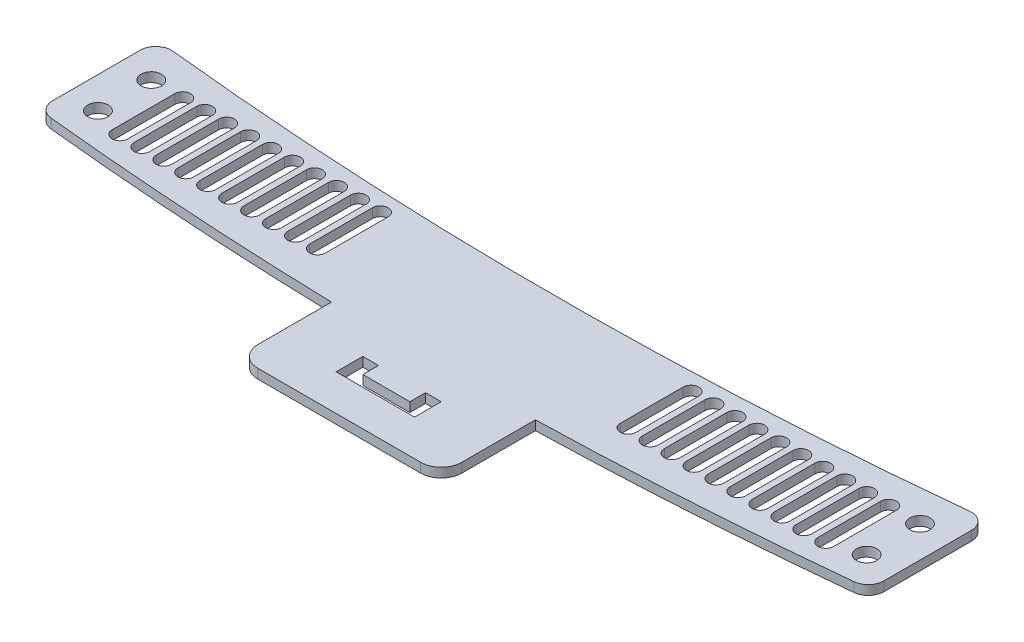
SolidWorks part; units mm, degrees
ref_plane "Front Plane" through (0, 0, 0) normal (0, 0, 1) x (1, 0, 0)
ref_plane "Top Plane" through (0, 0, 0) normal (0, 1, 0) x (1, 0, 0)
ref_plane "Right Plane" through (0, 0, 0) normal (1, 0, 0) x (0, 0, -1)
sketch "Sketch1" plane through (0, 0, 0) normal (0, 1, 0) x (1, 0, 0)
  line L0 (-10, 6.4366) -> (-10, -21.4937)
  line L5 (255, 6.4366) -> (255, -21.4937)
  line L6 (10, 0) -> (10, -20) construction
  line L7 (12.5, 0) -> (12.5, -20)
  line L8 (7.5, 0) -> (7.5, -20)
  line L9 (17, 0) -> (17, -20) construction
  line L10 (19.5, 0) -> (19.5, -20)
  line L11 (14.5, 0) -> (14.5, -20)
  line L12 (24, 0) -> (24, -20) construction
  line L13 (26.5, 0) -> (26.5, -20)
  line L14 (21.5, 0) -> (21.5, -20)
  line L15 (31, 0) -> (31, -20) construction
  line L16 (33.5, 0) -> (33.5, -20)
  line L17 (28.5, 0) -> (28.5, -20)
  line L18 (38, 0) -> (38, -20) construction
  line L19 (40.5, 0) -> (40.5, -20)
  line L20 (35.5, 0) -> (35.5, -20)
  line L21 (45, 0) -> (45, -20) construction
  line L22 (47.5, 0) -> (47.5, -20)
  line L23 (42.5, 0) -> (42.5, -20)
  line L24 (52, 0) -> (52, -20) construction
  line L25 (54.5, 0) -> (54.5, -20)
  line L26 (49.5, 0) -> (49.5, -20)
  line L27 (59, 0) -> (59, -20) construction
  line L28 (61.5, 0) -> (61.5, -20)
  line L29 (56.5, 0) -> (56.5, -20)
  line L30 (66, 0) -> (66, -20) construction
  line L31 (68.5, 0) -> (68.5, -20)
  line L32 (63.5, 0) -> (63.5, -20)
  line L33 (73, 0) -> (73, -20) construction
  line L34 (75.5, 0) -> (75.5, -20)
  line L35 (70.5, 0) -> (70.5, -20)
  line L36 (172, 0) -> (172, -20) construction
  line L37 (174.5, 0) -> (174.5, -20)
  line L38 (169.5, 0) -> (169.5, -20)
  line L39 (179, 0) -> (179, -20) construction
  line L40 (181.5, 0) -> (181.5, -20)
  line L41 (176.5, 0) -> (176.5, -20)
  line L42 (186, 0) -> (186, -20) construction
  line L43 (188.5, 0) -> (188.5, -20)
  line L44 (183.5, 0) -> (183.5, -20)
  line L45 (193, 0) -> (193, -20) construction
  line L46 (195.5, 0) -> (195.5, -20)
  line L47 (190.5, 0) -> (190.5, -20)
  line L48 (200, 0) -> (200, -20) construction
  line L49 (202.5, 0) -> (202.5, -20)
  line L50 (197.5, 0) -> (197.5, -20)
  line L51 (207, 0) -> (207, -20) construction
  line L52 (209.5, 0) -> (209.5, -20)
  line L53 (204.5, 0) -> (204.5, -20)
  line L54 (214, 0) -> (214, -20) construction
  line L55 (216.5, 0) -> (216.5, -20)
  line L56 (211.5, 0) -> (211.5, -20)
  line L57 (221, 0) -> (221, -20) construction
  line L58 (223.5, 0) -> (223.5, -20)
  line L59 (218.5, 0) -> (218.5, -20)
  line L60 (228, 0) -> (228, -20) construction
  line L61 (230.5, 0) -> (230.5, -20)
  line L62 (225.5, 0) -> (225.5, -20)
  line L63 (235, 0) -> (235, -20) construction
  line L64 (237.5, 0) -> (237.5, -20)
  line L65 (232.5, 0) -> (232.5, -20)
  line L66 (90, -32.58) -> (90, -56.0296)
  line L67 (96.5504, -62.58) -> (148.4496, -62.58)
  line L68 (155, -56.0296) -> (155, -32.58)
  line L69 (115, -42.58) -> (115, -47.58)
  line L70 (110, -42.58) -> (115, -42.58)
  line L71 (110, -42.58) -> (110, -51.08)
  line L72 (110, -51.08) -> (135, -51.08)
  line L73 (135, -42.58) -> (135, -51.08)
  line L74 (115, -47.58) -> (130, -47.58)
  line L75 (130, -47.58) -> (130, -42.58)
  line L76 (130, -42.58) -> (135, -42.58)
  circle A0 centre (0, 0) radius 3.25
  circle A1 centre (245, 0) radius 3.25
  circle A2 centre (0, -17) radius 3.25
  circle A3 centre (245, -17) radius 3.25
  arc A4 (-5.509, -26.4677) -> (90, -32.58) centre (122.5, 1224.5179) ccw
  arc A5 (-4.4795, 11.4094) -> (249.4795, 11.4094) centre (122.5, 1224.5179) ccw
  arc A6 (12.5, 0) -> (7.5, 0) centre (10, 0) ccw
  arc A7 (7.5, -20) -> (12.5, -20) centre (10, -20) ccw
  arc A8 (19.5, 0) -> (14.5, 0) centre (17, 0) ccw
  arc A9 (14.5, -20) -> (19.5, -20) centre (17, -20) ccw
  arc A10 (26.5, 0) -> (21.5, 0) centre (24, 0) ccw
  arc A11 (21.5, -20) -> (26.5, -20) centre (24, -20) ccw
  arc A12 (33.5, 0) -> (28.5, 0) centre (31, 0) ccw
  arc A13 (28.5, -20) -> (33.5, -20) centre (31, -20) ccw
  arc A14 (40.5, 0) -> (35.5, 0) centre (38, 0) ccw
  arc A15 (35.5, -20) -> (40.5, -20) centre (38, -20) ccw
  arc A16 (47.5, 0) -> (42.5, 0) centre (45, 0) ccw
  arc A17 (42.5, -20) -> (47.5, -20) centre (45, -20) ccw
  arc A18 (54.5, 0) -> (49.5, 0) centre (52, 0) ccw
  arc A19 (49.5, -20) -> (54.5, -20) centre (52, -20) ccw
  arc A20 (61.5, 0) -> (56.5, 0) centre (59, 0) ccw
  arc A21 (56.5, -20) -> (61.5, -20) centre (59, -20) ccw
  arc A22 (68.5, 0) -> (63.5, 0) centre (66, 0) ccw
  arc A23 (63.5, -20) -> (68.5, -20) centre (66, -20) ccw
  arc A24 (75.5, 0) -> (70.5, 0) centre (73, 0) ccw
  arc A25 (70.5, -20) -> (75.5, -20) centre (73, -20) ccw
  arc A26 (174.5, 0) -> (169.5, 0) centre (172, 0) ccw
  arc A27 (169.5, -20) -> (174.5, -20) centre (172, -20) ccw
  arc A28 (181.5, 0) -> (176.5, 0) centre (179, 0) ccw
  arc A29 (176.5, -20) -> (181.5, -20) centre (179, -20) ccw
  arc A30 (188.5, 0) -> (183.5, 0) centre (186, 0) ccw
  arc A31 (183.5, -20) -> (188.5, -20) centre (186, -20) ccw
  arc A32 (195.5, 0) -> (190.5, 0) centre (193, 0) ccw
  arc A33 (190.5, -20) -> (195.5, -20) centre (193, -20) ccw
  arc A34 (202.5, 0) -> (197.5, 0) centre (200, 0) ccw
  arc A35 (197.5, -20) -> (202.5, -20) centre (200, -20) ccw
  arc A36 (209.5, 0) -> (204.5, 0) centre (207, 0) ccw
  arc A37 (204.5, -20) -> (209.5, -20) centre (207, -20) ccw
  arc A38 (216.5, 0) -> (211.5, 0) centre (214, 0) ccw
  arc A39 (211.5, -20) -> (216.5, -20) centre (214, -20) ccw
  arc A40 (223.5, 0) -> (218.5, 0) centre (221, 0) ccw
  arc A41 (218.5, -20) -> (223.5, -20) centre (221, -20) ccw
  arc A42 (230.5, 0) -> (225.5, 0) centre (228, 0) ccw
  arc A43 (225.5, -20) -> (230.5, -20) centre (228, -20) ccw
  arc A44 (237.5, 0) -> (232.5, 0) centre (235, 0) ccw
  arc A45 (232.5, -20) -> (237.5, -20) centre (235, -20) ccw
  arc A46 (-10, -21.4937) -> (-5.509, -26.4677) centre (-5, -21.4937) ccw
  arc A47 (250.509, -26.4677) -> (255, -21.4937) centre (250, -21.4937) ccw
  arc A48 (255, 6.4366) -> (249.4795, 11.4094) centre (250, 6.4366) ccw
  arc A49 (-10, 6.4366) -> (-4.4795, 11.4094) centre (-5, 6.4366) cw
  arc A50 (155, -56.0296) -> (148.4496, -62.58) centre (148.4496, -56.0296) cw
  arc A51 (90, -56.0296) -> (96.5504, -62.58) centre (96.5504, -56.0296) ccw
  arc A52 (155, -32.58) -> (250.509, -26.4677) centre (122.5, 1224.5179) ccw
  point P14 (172, -10)
  point P18 (122.5, 4.7819)
  point P19 (10, -10)
  point P27 (17, -10)
  point P34 (24, -10)
  point P41 (31, -10)
  point P48 (38, -10)
  point P55 (45, -10)
  point P57 (10, 2.5)
  point P58 (10, -22.5)
  point P64 (52, -10)
  point P71 (59, -10)
  point P78 (66, -10)
  point P85 (73, -10)
  point P101 (179, -10)
  point P108 (186, -10)
  point P115 (193, -10)
  point P122 (200, -10)
  point P129 (207, -10)
  point P131 (172, 2.5)
  point P132 (172, -22.5)
  point P138 (214, -10)
  point P145 (221, -10)
  point P152 (228, -10)
  point P159 (235, -10)
  point P169 (-10, -26)
  point P172 (255, -26)
  point P175 (255, 12)
  point P179 (122.5, -62.58)
  point P188 (122.5, -51.08)
  dimension "D3" = 6.5
  dimension "D33" = 5
  dimension "D36" = 6.5504
  dimension "D1" = 245
  dimension "D2" = 17
  dimension "D5" = 9
  dimension "D6" = 10
  dimension "D7" = 10
  dimension "D8" = 12
  dimension "D12" = 25
  dimension "D13" = 5
  dimension "D14" = 2
  dimension "D15" = 2
  dimension "D16" = 2
  dimension "D17" = 2
  dimension "D18" = 2
  dimension "D19" = 2
  dimension "D20" = 2
  dimension "D21" = 2
  dimension "D22" = 2
  dimension "D9" = 10
  dimension "D10" = 25
  dimension "D11" = 5
  dimension "D23" = 2
  dimension "D24" = 2
  dimension "D25" = 2
  dimension "D26" = 2
  dimension "D27" = 2
  dimension "D28" = 2
  dimension "D29" = 2
  dimension "D30" = 2
  dimension "D31" = 2
  dimension "D32" = 10
  dimension "D34" = 65
  dimension "D4" = 6.6275
  dimension "D35" = 25
  dimension "D37" = 3.5
  dimension "D38" = 5
  dimension "D39" = 15
  dimension "D40" = 10
  dimension "D41" = 30
extrude "Boss-Extrude1" add sketch "Sketch1" along normal blind 3
equation "\"D7@Sketch1\"=\"D6@Sketch1\""
equation "\"D15@Sketch1\"=\"D14@Sketch1\""
equation "\"D16@Sketch1\"=\"D14@Sketch1\""
equation "\"D17@Sketch1\"=\"D14@Sketch1\""
equation "\"D18@Sketch1\"=\"D14@Sketch1\""
equation "\"D19@Sketch1\"=\"D14@Sketch1\""
equation "\"D20@Sketch1\"=\"D14@Sketch1\""
equation "\"D21@Sketch1\"=\"D14@Sketch1\""
equation "\"D22@Sketch1\"=\"D14@Sketch1\""
equation "\"D10@Sketch1\"=\"D12@Sketch1\""
equation "\"D11@Sketch1\"=\"D13@Sketch1\""
equation "\"D32@Sketch1\"=\"D9@Sketch1\""
